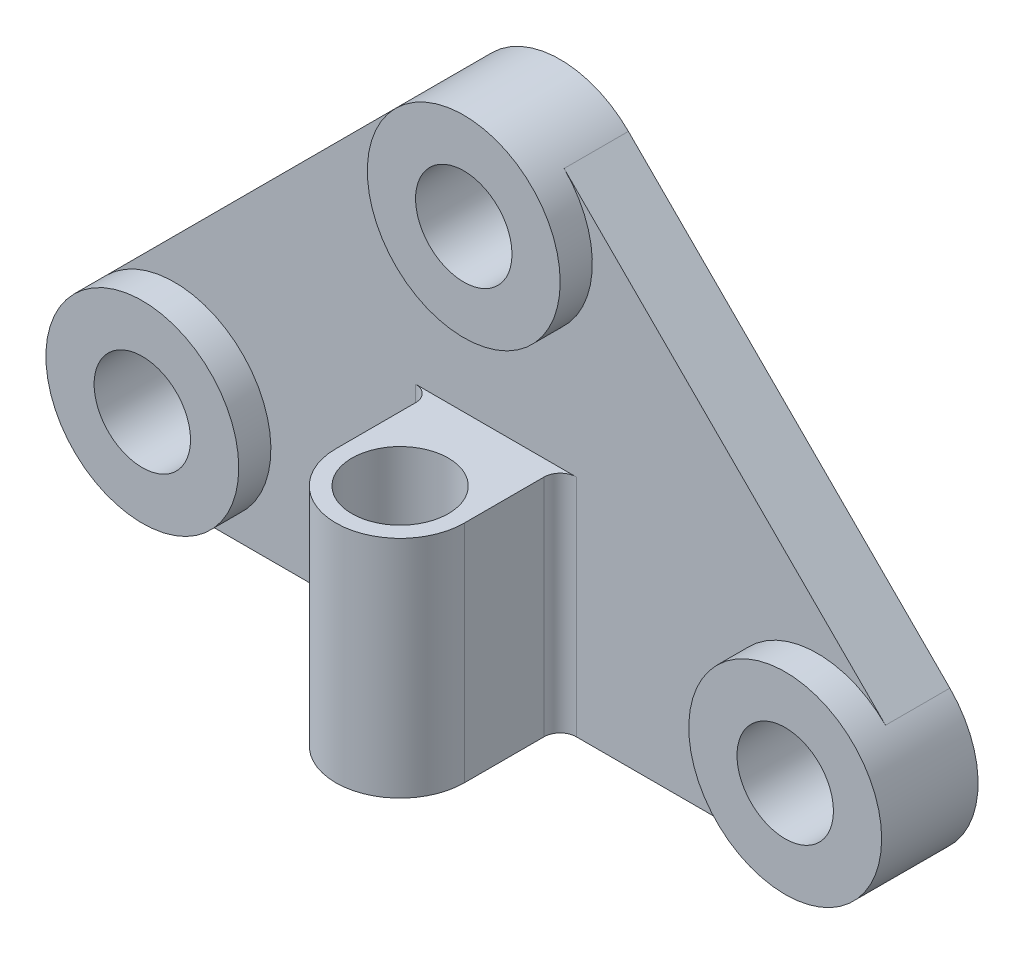
SolidWorks part; units mm, degrees
ref_plane "Front Plane" through (0, 0, 0) normal (0, 0, 1) x (1, 0, 0)
ref_plane "Top Plane" through (0, 0, 0) normal (0, 1, 0) x (1, 0, 0)
ref_plane "Right Plane" through (0, 0, 0) normal (1, 0, 0) x (0, 0, -1)
sketch "Sketch2" plane through (0, 0, 0) normal (0, 0, 1) x (1, 0, 0)
  line L0 (-100, -30) -> (100, -30)
  line L1 (-121.2132, 21.2132) -> (-21.2132, 121.2132)
  line L2 (121.2132, 21.2132) -> (21.2132, 121.2132)
  arc A0 (100, -30) -> (121.2132, 21.2132) centre (100, 0) ccw
  circle A1 centre (100, 0) radius 15
  arc A2 (-121.2132, 21.2132) -> (-100, -30) centre (-100, 0) ccw
  circle A3 centre (-100, 0) radius 15
  circle A4 centre (0, 100) radius 15
  arc A5 (21.2132, 121.2132) -> (-21.2132, 121.2132) centre (0, 100) ccw
  dimension "D1" = 30
  dimension "D2" = 60
  dimension "D3" = 100
  dimension "D4" = 100
  dimension "D5" = 100
extrude "Boss-Extrude2" add sketch "Sketch2" along normal blind 20
sketch "Sketch3" plane through (0, 0, 20) normal (0, 0, 1) x (1, 0, 0)
  circle A0 centre (-100, 0) radius 15
  circle A1 centre (-100, 0) radius 30
  circle A2 centre (100, 0) radius 15
  circle A3 centre (100, 0) radius 30
  circle A4 centre (0, 100) radius 15
  circle A5 centre (0, 100) radius 30
  dimension "D1" = 30
  dimension "D2" = 60
extrude "Boss-Extrude3" add sketch "Sketch3" along normal blind 10
sketch "Sketch4" plane through (0, -30, 0) normal (0, -1, 0) x (1, 0, 0)
  line L0 (20, 49.8) -> (20, 20)
  line L1 (30, 20) -> (-30, 20) construction
  line L2 (20, 20) -> (-20, 20)
  line L3 (-100, 20) -> (100, 20) construction
  line L4 (-20, 20) -> (-20, 49.8)
  circle A0 centre (0, 49.8) radius 15
  arc A1 (20, 49.8) -> (-20, 49.8) centre (0, 49.8) ccw
  dimension "D1" = 30
  dimension "D2" = 40
  dimension "D3" = 49.8
extrude "Boss-Extrude4" add sketch "Sketch4" against normal blind 70
fillet "Fillet1" radius 5 1 edges at (20, 5, 20)
fillet "Fillet2" radius 5 1 edges at (-20, 5, 20)
